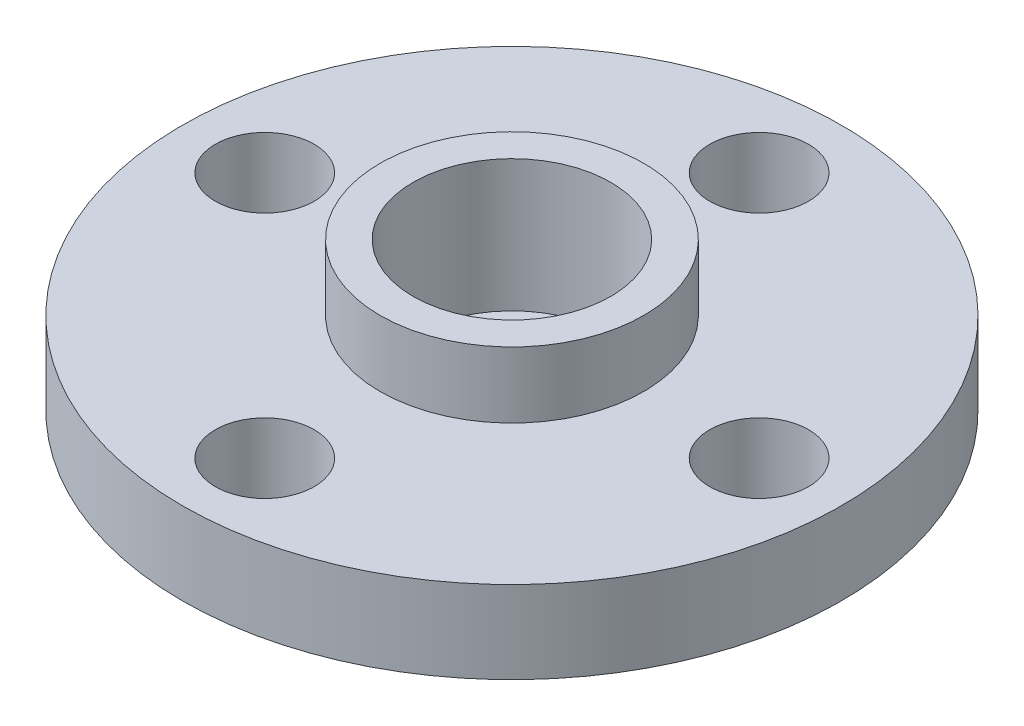
SolidWorks part; units mm, degrees
material "Chrome Stainless Steel"
ref_plane "Front Plane" through (0, 0, 0) normal (0, 0, 1) x (1, 0, 0)
ref_plane "Top Plane" through (0, 0, 0) normal (0, 1, 0) x (1, 0, 0)
ref_plane "Right Plane" through (0, 0, 0) normal (1, 0, 0) x (0, 0, -1)
sketch "Sketch1" plane through (0, 0, 0) normal (0, 0, 1) x (1, 0, 0)
  line L0 (0, 3.4245) -> (0, 0) construction
  line L1 (3, 0) -> (4, 0)
  line L2 (4, 0) -> (4, -2)
  line L3 (4, -2) -> (10, -2)
  line L4 (10, -2) -> (10, -4.5)
  line L5 (10, -4.5) -> (1.5, -4.5)
  line L6 (0, -4.5) -> (0, 0) construction
  line L7 (3, 0) -> (3, -4)
  line L8 (3, -4) -> (1.5, -4)
  line L9 (1.5, -4) -> (1.5, -4.5)
  line L10 (1.5, -4.5) -> (0, -4.5) construction
  line L11 (0, 0) -> (0, -4.5) construction
  line L12 (0, -4.5) -> (0, -6.9835) construction
  line L13 (0, 0) -> (3, 0) construction
  dimension "D1" = 10
  dimension "D2" = 4
  dimension "D3" = 3
  dimension "D4" = 2
  dimension "D5" = 2.5
  dimension "D6" = 0.5
  dimension "D7" = 1.5
revolve "Revolve1" add sketch "Sketch1" angle 360 about L0
sketch "Sketch2" plane through (0, -4.5, 0) normal (0, -1, 0) x (1, 0, 0)
  line L0 (0, 0) -> (0, -11.3657) construction
  line L1 (-7.8096, 0) -> (7.8096, 0) construction
  circle A0 centre (0, -7.5) radius 1.5
  circle A1 centre (-7.5, 0) radius 1.5
  circle A2 centre (0, 7.5) radius 1.5
  circle A3 centre (7.5, 0) radius 1.5
  point P14 (0, 0)
  point P15 (0, 0)
  dimension "D1" = 3
  dimension "D2" = 7.5
  dimension "D3" = 4
extrude "Cut-Extrude1" cut sketch "Sketch2" against normal blind 10
